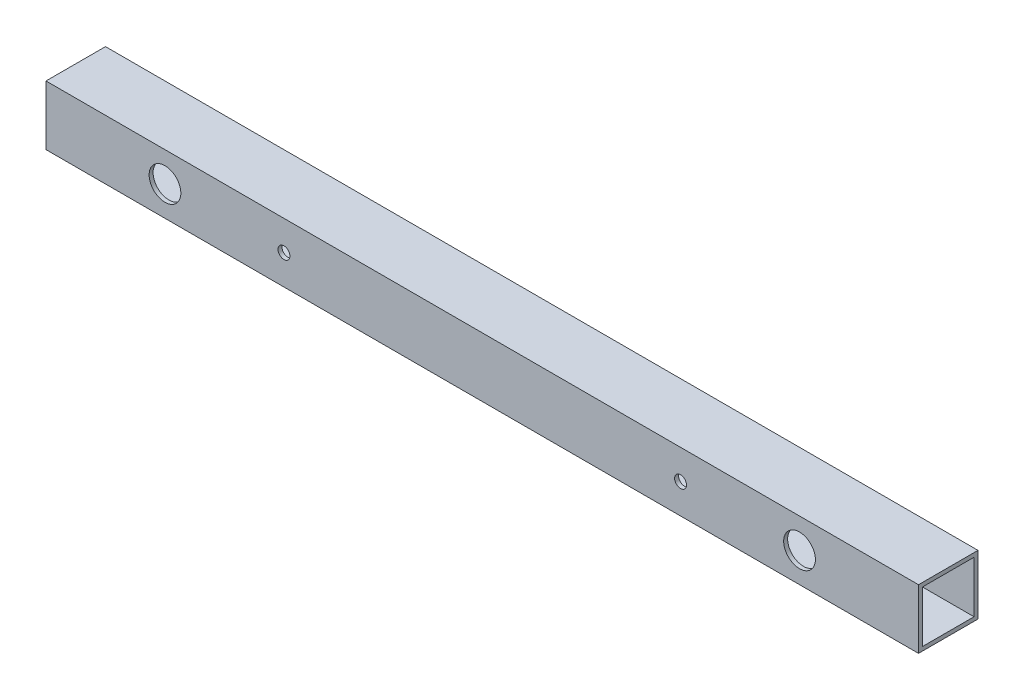
SolidWorks part; units mm, degrees
ref_plane "前视基准面" through (0, 0, 0) normal (0, 0, 1) x (1, 0, 0)
ref_plane "上视基准面" through (0, 0, 0) normal (0, 1, 0) x (1, 0, 0)
ref_plane "右视基准面" through (0, 0, 0) normal (1, 0, 0) x (0, 0, -1)
sketch "草图1" plane through (0, 0, 0) normal (1, 0, 0) x (0, 0, -1)
  line L0 (-6.5, 6.5) -> (6.5, 6.5)
  line L1 (-7.5, -7.5) -> (7.5, -7.5)
  line L2 (-7.5, -7.5) -> (-7.5, 7.5)
  line L3 (-7.5, 7.5) -> (7.5, 7.5)
  line L4 (7.5, -7.5) -> (7.5, 7.5)
  line L5 (-7.5, -7.5) -> (7.5, 7.5) construction
  line L6 (-7.5, 7.5) -> (7.5, -7.5) construction
  line L7 (6.5, -6.5) -> (6.5, 6.5)
  line L8 (-6.5, -6.5) -> (6.5, -6.5)
  line L9 (-6.5, -6.5) -> (-6.5, 6.5)
  point P0 (0, 0)
  dimension "D1" = 15
  dimension "D2" = 15
  dimension "D3" = 1
extrude "凸台-拉伸1" add sketch "草图1" along normal blind 220
sketch "草图2" plane through (0, 0, -7.5) normal (0, 0, -1) x (-1, 0, 0)
  line L0 (0, -7.5) -> (0, 7.5) construction
  line L2 (-110, 16.2034) -> (-110, -20.9505) construction
  circle A0 centre (-30, 0) radius 1.5
  circle A1 centre (-60, 0) radius 1.5
  circle A2 centre (-160, 0) radius 1.5
  circle A3 centre (-190, 0) radius 1.5
  dimension "D1" = 30
  dimension "D2" = 60
extrude "切除-拉伸4" cut sketch "草图2" against normal through all
sketch "草图5" plane through (0, 0, -7.5) normal (0, 0, -1) x (-1, 0, 0)
  circle A0 centre (-160, 0) radius 4
  circle A1 centre (-60, 0) radius 4
extrude "切除-拉伸5" cut sketch "草图5" against normal blind 10
sketch "草图6" plane through (0, 0, 7.5) normal (0, 0, 1) x (1, 0, 0)
  circle A0 centre (190, 0) radius 4
  circle A1 centre (30, 0) radius 4
extrude "切除-拉伸6" cut sketch "草图6" against normal blind 10
